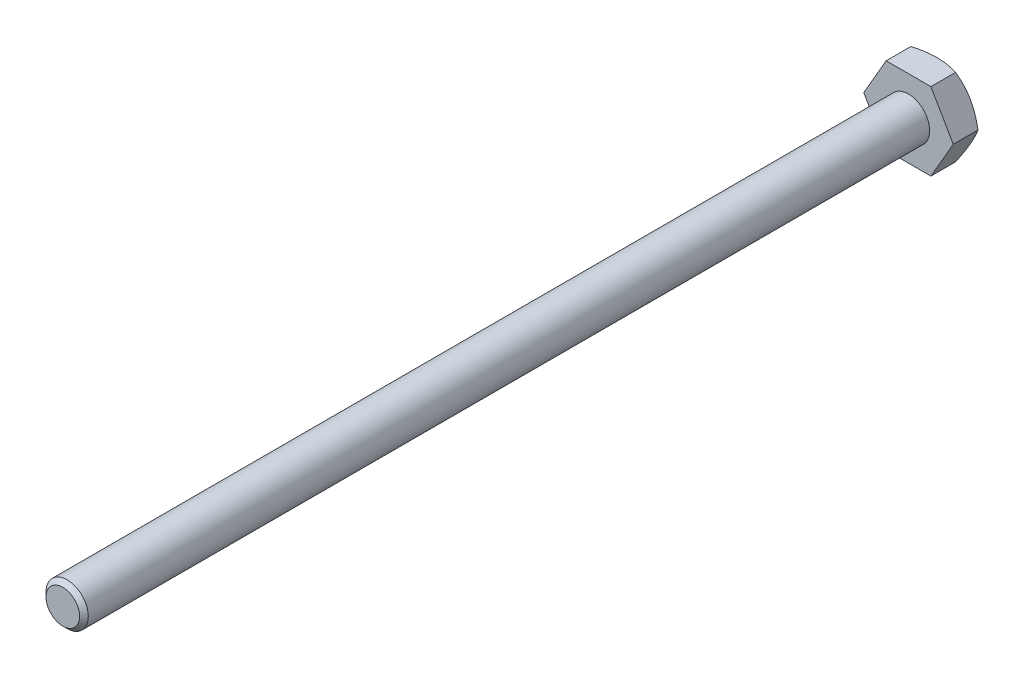
SolidWorks part; units mm, degrees
material "Plain Carbon Steel"
ref_plane "Front Plane" through (0, 0, 0) normal (0, 0, 1) x (1, 0, 0)
ref_plane "Top Plane" through (0, 0, 0) normal (0, 1, 0) x (1, 0, 0)
ref_plane "Right Plane" through (0, 0, 0) normal (1, 0, 0) x (0, 0, -1)
sketch "Sketch1" plane through (0, 0, 0) normal (0, 0, 1) x (1, 0, 0)
  line L1 (3.1754, 0) -> (1.5877, 2.75)
  line L2 (1.5877, 2.75) -> (-1.5877, 2.75)
  line L3 (-1.5877, 2.75) -> (-3.1754, 0)
  line L4 (-3.1754, 0) -> (-1.5877, -2.75)
  line L5 (-1.5877, -2.75) -> (1.5877, -2.75)
  line L6 (1.5877, -2.75) -> (3.1754, 0)
  circle A0 centre (0, 0) radius 2.75 construction
  dimension "D1" = 5.5
extrude "Extrude1" add sketch "Sketch1" along normal blind 2
sketch "Sketch2" plane through (0, 0, 2) normal (0, 0, 1) x (1, 0, 0)
  circle A0 centre (0, 0) radius 1.5
  dimension "D1" = 3
extrude "Extrude2" add sketch "Sketch2" along normal blind 60
cosmetic thread "Cosmetic Thread1" parameters "D2"=2.386
sketch "Sketch3" plane through (0, 0, 0) normal (1, 0, 0) x (0, 0, -1)
  line L0 (0, 2.75) -> (0, 102.75)
  line L1 (0, 102.75) -> (-57.735, 102.75)
  line L2 (-57.735, 102.75) -> (0, 2.75)
  line L3 (0, 0) -> (11.4679, 0) construction
  dimension "D1" = 30
  dimension "D2" = 100
revolve "Cut-Revolve1" cut sketch "Sketch3" angle 360 about L3
chamfer "Chamfer1" distance 0.307 angle 45 1 edges at (1.5, 0, 62)
